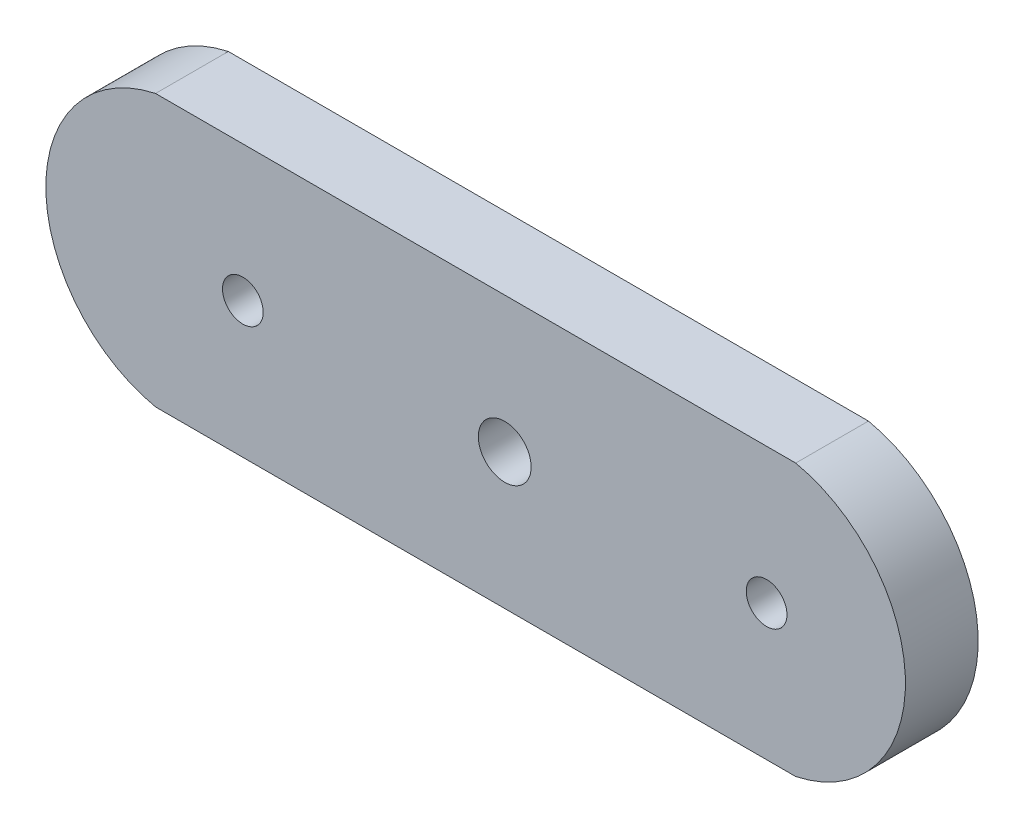
SolidWorks part; units mm, degrees
ref_plane "Front Plane" through (0, 0, 0) normal (0, 0, 1) x (1, 0, 0)
ref_plane "Top Plane" through (0, 0, 0) normal (0, 1, 0) x (1, 0, 0)
ref_plane "Right Plane" through (0, 0, 0) normal (1, 0, 0) x (0, 0, -1)
ref_plane "Plane9" through (0, 0, 0) normal (0, 0, 1) x (1, 0, 0)
sketch "Sketch9" plane through (0, 0, 0) normal (0, 0, 1) x (1, 0, 0)
  line L0 (19.05, 0) -> (69.85, 0)
  line L1 (69.85, 23.6985) -> (19.05, 23.6985)
  line L2 (44.45, 0) -> (44.45, 23.6985) construction
  line L3 (19.05, 23.6985) -> (13.97, 23.6985)
  line L4 (19.05, 0) -> (13.97, 0)
  circle A0 centre (44.45, 11.8493) radius 2.305
  circle A1 centre (67.31, 11.8493) radius 1.778
  circle A2 centre (21.59, 11.8493) radius 1.778
  arc A3 (13.97, 0) -> (13.97, 23.6985) centre (16.51, 11.8493) cw
  arc A4 (69.85, 0) -> (69.85, 23.6985) centre (67.31, 11.8493) ccw
  point P4 (44.45, 23.6985)
  point P5 (44.45, 11.8493)
  dimension "D1" = 4.61
  dimension "D5" = 3.556
  dimension "D6" = 3.556
  dimension "D7" = 5.08
  dimension "D2" = 22.86
  dimension "D3" = 50.8
  dimension "D4" = 22.86
extrude "Boss-Extrude1" add sketch "Sketch9" along normal blind 6.35
